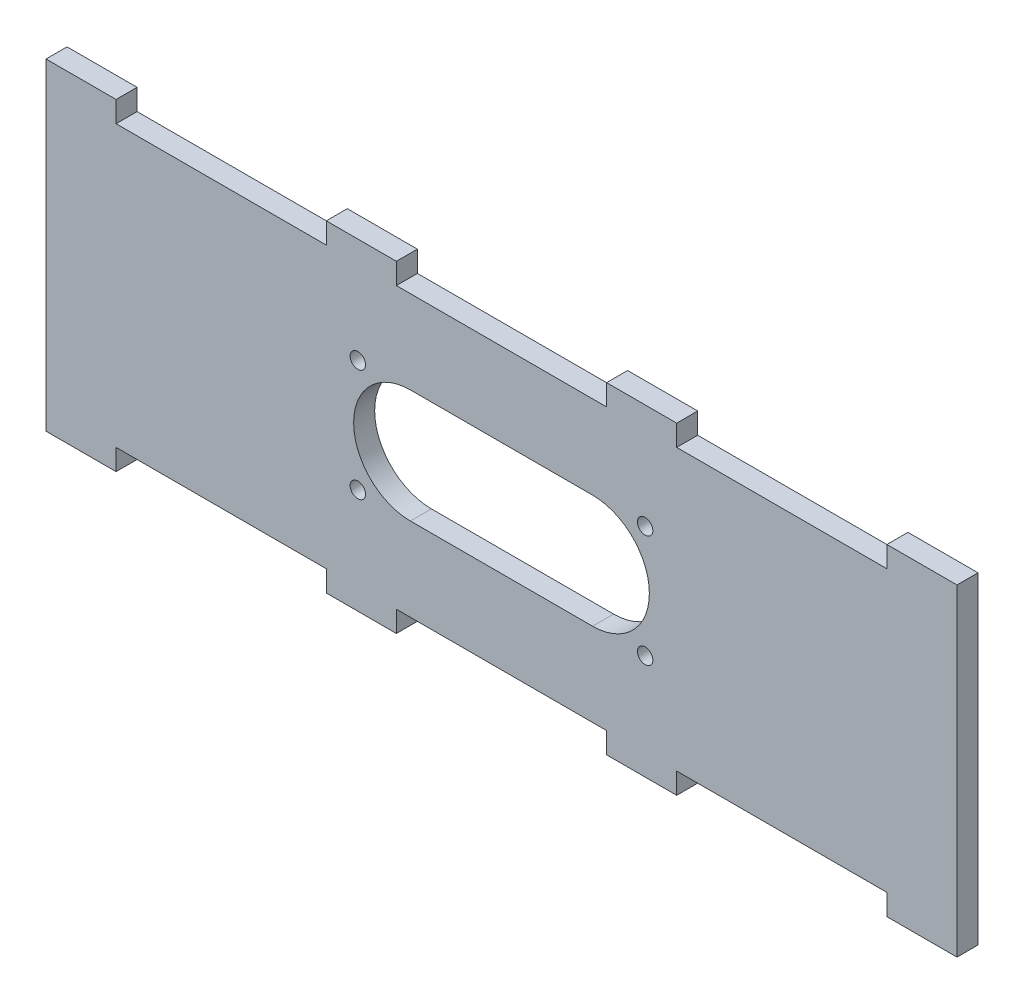
SolidWorks part; units mm, degrees
ref_plane "Front Plane" through (0, 0, 0) normal (0, 0, 1) x (1, 0, 0)
ref_plane "Top Plane" through (0, 0, 0) normal (0, 1, 0) x (1, 0, 0)
ref_plane "Right Plane" through (0, 0, 0) normal (1, 0, 0) x (0, 0, -1)
sketch "Sketch1" plane through (0, 0, 0) normal (0, 0, 1) x (1, 0, 0)
  line L0 (-65, 0) -> (65, 0) construction
  line L1 (-65, 20) -> (65, 20)
  line L2 (-65, 20) -> (-65, -20)
  line L3 (-65, -20) -> (65, -20)
  line L4 (65, 20) -> (65, -20)
  line L5 (-65, 20) -> (-55, 20)
  line L6 (-65, 20) -> (-65, 23)
  line L7 (-65, 23) -> (-55, 23)
  line L8 (-55, 20) -> (-55, 23)
  line L9 (65, 20) -> (55, 20)
  line L10 (65, 20) -> (65, 23)
  line L11 (65, 23) -> (55, 23)
  line L12 (55, 20) -> (55, 23)
  line L13 (-25, 20) -> (-15, 20)
  line L14 (-25, 20) -> (-25, 23)
  line L15 (-25, 23) -> (-15, 23)
  line L16 (-15, 20) -> (-15, 23)
  line L17 (25, 20) -> (15, 20)
  line L18 (25, 20) -> (25, 23)
  line L19 (25, 23) -> (15, 23)
  line L20 (15, 20) -> (15, 23)
  line L21 (65, -23) -> (55, -23)
  line L22 (55, -20) -> (55, -23)
  line L23 (65, -20) -> (55, -20)
  line L24 (65, -20) -> (65, -23)
  line L25 (25, -23) -> (15, -23)
  line L26 (15, -20) -> (15, -23)
  line L27 (25, -20) -> (15, -20)
  line L28 (25, -20) -> (25, -23)
  line L29 (-25, -23) -> (-15, -23)
  line L30 (-15, -20) -> (-15, -23)
  line L31 (-25, -20) -> (-15, -20)
  line L32 (-25, -20) -> (-25, -23)
  line L33 (-65, -23) -> (-55, -23)
  line L34 (-55, -20) -> (-55, -23)
  line L35 (-65, -20) -> (-55, -20)
  line L36 (-65, -20) -> (-65, -23)
  point P4 (0, 20)
  point P6 (-65, 0)
  point P21 (-60, 23)
  point P22 (-20, 23)
  point P23 (60, 23)
  point P24 (20, 23)
  dimension "D1" = 40
  dimension "D2" = 130
  dimension "D3" = 10
  dimension "D4" = 3
  dimension "D5" = 40
  dimension "D6" = 40
extrude "Boss-Extrude1" add sketch "Sketch1" along normal blind 3 contours L2 L0 L4 L1 | L0 L2 L3 L4 | L1 L8 L7 L6 | L1 L16 L15 L14 | L20 L1 L18 L19 | L12 L1 L10 L11 | L24 L3 L22 L21 | L28 L3 L26 L25 | L3 L32 L29 L30 | L3 L36 L33 L34
sketch "Sketch4" plane through (0, 0, 3) normal (0, 0, 1) x (1, 0, 0)
  point P0 (0, 0)
  line B0 (-13, 8.1) -> (13, 8.1)
  line B1 (-13, -8.1) -> (13, -8.1)
  arc B2 (-13, 8.1) -> (-13, -8.1) centre (-13, 0) ccw
  arc B3 (13, -8.1) -> (13, 8.1) centre (13, 0) ccw
  circle B4 centre (-20.5, 8) radius 1.1
  circle B5 centre (-20.5, -8) radius 1.1
  circle B6 centre (20.5, 8) radius 1.1
  circle B7 centre (20.5, -8) radius 1.1
sketch_block_instance "Block-SRF05-1"
sketch_block "Block1" parameters "D4"=16.2, "D5"=2.2, "D1"=45, "D2"=20, "D3"=26, "D6"=2, "D7"=2, "D8"=2, "D9"=2
extrude "Cut-Extrude2" cut sketch "Sketch4" against normal through all
